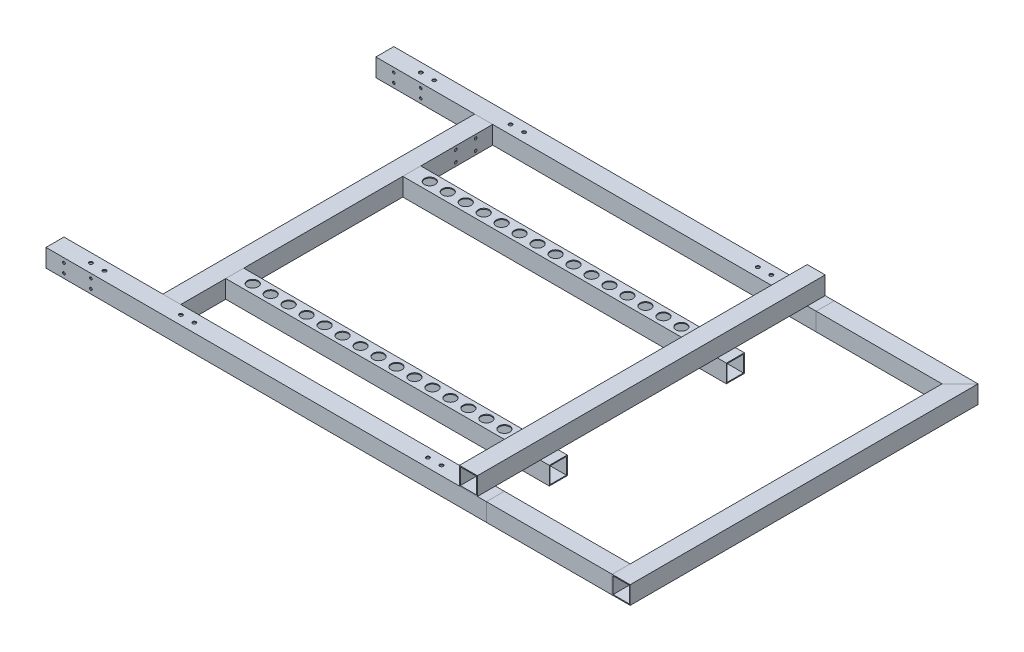
SolidWorks part; units mm, degrees
material "6063-O"
ref_plane "Front" through (0, 0, 0) normal (0, 0, 1) x (1, 0, 0)
ref_plane "Top" through (0, 0, 0) normal (0, 1, 0) x (1, 0, 0)
ref_plane "Right" through (0, 0, 0) normal (1, 0, 0) x (0, 0, -1)
sketch "草图1" plane through (0, 0, 0) normal (0, 1, 0) x (1, 0, 0)
  line L0 (0, 0) -> (500, 0)
  line L1 (0, -367) -> (500, -367)
  line L2 (0, -367) -> (0, -447)
  line L3 (0, -447) -> (500, -447)
  line L4 (130, 0) -> (130, -367)
  line L5 (130, -367) -> (130, -447)
  dimension "D1" = 447
  dimension "D2" = 80
  dimension "D3" = 500
  dimension "D4" = 130
other "铝管 20X20X1(1)"
ref_plane "基准面1" through (0, 0, 0) normal (1, 0, 0) x (0, 0, -1)
sketch "草图11" plane through (0, 0, 0) normal (1, 0, 0) x (0, 0, -1)
  line L1 (-10, -10) -> (10, -10)
  line L2 (-10, -10) -> (-10, 10)
  line L3 (-10, 10) -> (10, 10)
  line L4 (10, -10) -> (10, 10)
  line L5 (-10, -10) -> (10, 10) construction
  line L6 (-10, 10) -> (10, -10) construction
  line L7 (-9, -9) -> (9, -9)
  line L8 (-9, -9) -> (-9, 9)
  line L9 (-9, 9) -> (9, 9)
  line L10 (9, -9) -> (9, 9)
  line L11 (-9, -9) -> (9, 9) construction
  line L12 (-9, 9) -> (9, -9) construction
  point P0 (0, 0)
  point P6 (0, 0)
  point P11 (0, 0)
  dimension "D1" = 20
  dimension "D2" = 20
  dimension "D3" = 18
  dimension "D4" = 18
sketch "草图12" plane through (0, 0, 377) normal (0, 0, 1) x (1, 0, 0)
  line L0 (-10, -10) -> (-10, 10) construction
  line L1 (500, 10) -> (10, 10) construction
  circle A0 centre (30, 5) radius 1.5
  circle A1 centre (60, 5) radius 1.5
  circle A2 centre (30, -5) radius 1.5
  circle A3 centre (60, -5) radius 1.5
  dimension "D1" = 3
  dimension "D2" = 3
  dimension "D3" = 40
  dimension "D4" = 30
  dimension "D5" = 5
  dimension "D6" = 2
extrude "切除-拉伸1" cut sketch "草图12" against normal through all
sketch "草图13" plane through (0, 0, 0) normal (0, 1, 0) x (1, 0, 0)
  line L0 (500, 0) -> (650, 0)
  line L1 (500, 10) -> (500, -10) construction
  line L2 (500, -447) -> (650, -447)
  line L3 (500, -457) -> (500, -437) construction
  line L4 (500, -367) -> (650, -367)
  line L5 (500, -357) -> (500, -377) construction
  line L6 (650, -447) -> (650, 0)
  dimension "D1" = 150
other "铝管 20X20X1(2)"
ref_plane "基准面2" through (500, 0, 447) normal (1, 0, 0) x (0, 0, -1)
sketch "草图14" plane through (500, 0, 447) normal (1, 0, 0) x (0, 0, -1)
  line L1 (-10, -10) -> (10, -10)
  line L2 (-10, -10) -> (-10, 10)
  line L3 (-10, 10) -> (10, 10)
  line L4 (10, -10) -> (10, 10)
  line L5 (-10, -10) -> (10, 10) construction
  line L6 (-10, 10) -> (10, -10) construction
  line L7 (-9, -9) -> (9, -9)
  line L8 (-9, -9) -> (-9, 9)
  line L9 (-9, 9) -> (9, 9)
  line L10 (9, -9) -> (9, 9)
  line L11 (-9, -9) -> (9, 9) construction
  line L12 (-9, 9) -> (9, -9) construction
  point P0 (0, 0)
  point P6 (0, 0)
  point P11 (0, 0)
  dimension "D1" = 20
  dimension "D2" = 20
  dimension "D3" = 18
  dimension "D4" = 18
ref_plane "基准面3" through (0, 20, 0) normal (0, 1, 0) x (1, 0, 0)
sketch "草图15" plane through (0, 20, 0) normal (0, 1, 0) x (1, 0, 0)
  line L0 (480, 10) -> (480, -457)
  line L1 (500, 10) -> (0, 10) construction
  line L2 (-10, -457) -> (500, -457) construction
  dimension "D1" = 20
other "铝管 20X20X1(3)"
ref_plane "基准面4" through (480, 20, -10) normal (0, 0, 1) x (1, 0, 0)
sketch "草图16" plane through (480, 20, -10) normal (0, 0, 1) x (1, 0, 0)
  line L1 (-10, -10) -> (10, -10)
  line L2 (-10, -10) -> (-10, 10)
  line L3 (-10, 10) -> (10, 10)
  line L4 (10, -10) -> (10, 10)
  line L5 (-10, -10) -> (10, 10) construction
  line L6 (-10, 10) -> (10, -10) construction
  line L7 (-9, -9) -> (9, -9)
  line L8 (-9, -9) -> (-9, 9)
  line L9 (-9, 9) -> (9, 9)
  line L10 (9, -9) -> (9, 9)
  line L11 (-9, -9) -> (9, 9) construction
  line L12 (-9, 9) -> (9, -9) construction
  point P0 (0, 0)
  point P6 (0, 0)
  point P11 (0, 0)
  dimension "D1" = 20
  dimension "D2" = 20
  dimension "D3" = 18
  dimension "D4" = 18
sketch "草图17" plane through (140, 0, 0) normal (1, 0, 0) x (0, 0, -1)
  line L0 (-407, 10) -> (-407, -10) construction
  line L1 (-437, 10) -> (-377, 10) construction
  line L2 (-437, -10) -> (-377, -10) construction
  line L4 (-10, 0) -> (-81.1967, 0) construction
  line L5 (-10, 10) -> (-10, -10) construction
  line L6 (-40, 10) -> (-40, -10) construction
  line L7 (-357, 10) -> (-10, 10) construction
  line L8 (-357, -10) -> (-10, -10) construction
  circle A0 centre (-418, 6) radius 1.5 construction
  circle A1 centre (-418, -6) radius 1.5 construction
  circle A2 centre (-396, -6) radius 1.5 construction
  circle A3 centre (-396, 6) radius 1.5 construction
  circle A4 centre (-51, 6) radius 1.5
  circle A5 centre (-51, -6) radius 1.5
  circle A6 centre (-29, 6) radius 1.5
  circle A7 centre (-29, -6) radius 1.5
  dimension "D1" = 3
  dimension "D2" = 3
  dimension "D7" = 3
  dimension "D8" = 3
  dimension "D9" = 3
  dimension "D10" = 3
  dimension "D3" = 4
  dimension "D4" = 12
  dimension "D5" = 11
  dimension "D6" = 30
  dimension "D11" = 22
  dimension "D12" = 12
sketch "草图18" plane through (0, 0, 0) normal (0, 1, 0) x (1, 0, 0)
  line L0 (140, -100) -> (500, -100)
  line L1 (140, -357) -> (140, -10) construction
  line L2 (140, -297) -> (500, -297)
  line L3 (500, -357) -> (-10, -357) construction
  line L4 (500, -10) -> (0, -10) construction
  line L5 (500, 10) -> (500, -10) construction
  dimension "D1" = 60
  dimension "D2" = 90
other "铝管 20X20X1(4)"
ref_plane "基准面5" through (140, 0, 100) normal (1, 0, 0) x (0, 0, -1)
sketch "草图110" plane through (140, 0, 100) normal (1, 0, 0) x (0, 0, -1)
  line L1 (-10, -10) -> (10, -10)
  line L2 (-10, -10) -> (-10, 10)
  line L3 (-10, 10) -> (10, 10)
  line L4 (10, -10) -> (10, 10)
  line L5 (-10, -10) -> (10, 10) construction
  line L6 (-10, 10) -> (10, -10) construction
  line L7 (-9, -9) -> (9, -9)
  line L8 (-9, -9) -> (-9, 9)
  line L9 (-9, 9) -> (9, 9)
  line L10 (9, -9) -> (9, 9)
  line L11 (-9, -9) -> (9, 9) construction
  line L12 (-9, 9) -> (9, -9) construction
  point P0 (0, 0)
  point P6 (0, 0)
  point P11 (0, 0)
  dimension "D1" = 20
  dimension "D2" = 20
  dimension "D3" = 18
  dimension "D4" = 18
sketch "草图111" plane through (0, 10, 0) normal (0, 1, 0) x (1, 0, 0)
  line L0 (140, -100) -> (500, -100) construction
  line L1 (140, -90) -> (140, -110) construction
  line L2 (500, -90) -> (500, -110) construction
  line L3 (140, -297) -> (500, -297) construction
  line L4 (140, -287) -> (140, -307) construction
  line L5 (500, -287) -> (500, -307) construction
  line L6 (140, -357) -> (140, -10) construction
  circle A0 centre (160, -100) radius 6
  circle A1 centre (160, -297) radius 6
  circle A2 centre (180, -100) radius 6
  circle A3 centre (180, -297) radius 6
  circle A4 centre (200, -100) radius 6
  circle A5 centre (200, -297) radius 6
  circle A6 centre (220, -100) radius 6
  circle A7 centre (220, -297) radius 6
  circle A8 centre (240, -100) radius 6
  circle A9 centre (240, -297) radius 6
  circle A10 centre (260, -100) radius 6
  circle A11 centre (260, -297) radius 6
  circle A12 centre (280, -100) radius 6
  circle A13 centre (280, -297) radius 6
  circle A14 centre (300, -100) radius 6
  circle A15 centre (300, -297) radius 6
  circle A16 centre (320, -100) radius 6
  circle A17 centre (320, -297) radius 6
  circle A18 centre (340, -100) radius 6
  circle A19 centre (340, -297) radius 6
  circle A20 centre (360, -100) radius 6
  circle A21 centre (360, -297) radius 6
  circle A22 centre (380, -100) radius 6
  circle A23 centre (380, -297) radius 6
  circle A24 centre (400, -100) radius 6
  circle A25 centre (400, -297) radius 6
  circle A26 centre (420, -100) radius 6
  circle A27 centre (420, -297) radius 6
  circle A28 centre (440, -100) radius 6
  circle A29 centre (440, -297) radius 6
  dimension "D1" = 12
  dimension "D2" = 12
  dimension "D3" = 20
  dimension "D4" = 20
  dimension "D5" = 15
extrude "切除-拉伸3" cut sketch "草图111" against normal through all
sketch "草图112" plane through (0, 0, 307) normal (0, 0, 1) x (1, 0, 0)
  circle A0 centre (462, 0) radius 1.5
  dimension "D1" = 3
extrude "切除-拉伸4" cut sketch "草图112" against normal up to surface (217 mm away)
extrude "切除-拉伸5" cut sketch "草图17" against normal through all
sketch "草图113" plane through (0, 0, 457) normal (0, 0, 1) x (1, 0, 0)
  line L0 (660, -10) -> (660, 10) construction
  line L1 (660, 10) -> (500, 10) construction
  line L2 (500, 10) -> (500, -10) construction
  line L3 (500, -10) -> (660, -10) construction
  line L4 (-10, 10) -> (-10, -10) construction
  line L5 (-10, -10) -> (500, -10) construction
  line L6 (500, -10) -> (500, 10) construction
  line L7 (500, 10) -> (-10, 10) construction
  line L8 (660, -10) -> (660, 10)
  line L9 (660, 10) -> (500, 10)
  line L10 (500, 10) -> (500, -10)
  line L11 (500, -10) -> (660, -10)
  line L12 (-10, 10) -> (-10, -10)
  line L13 (-10, -10) -> (500, -10)
  line L14 (500, -10) -> (500, 10)
  line L15 (500, 10) -> (-10, 10)
  line L17 (418.5326, 10) -> (518.891, 10)
  line L18 (418.5326, 10) -> (418.5326, 44.5746)
  line L19 (418.5326, 44.5746) -> (518.891, 44.5746)
  line L20 (518.891, 10) -> (518.891, 44.5746)
  line M1 (-10, 10) -> (-10, -10)
  line M2 (-10, -10) -> (500, -10)
  line M3 (500, -10) -> (500, 10)
  line M4 (500, 10) -> (-10, 10)
extrude "切除-拉伸7" cut sketch "草图113" against normal up to surface (80 mm away) contours L15 M4 M1 M2 M3 | L11 L8 L9 M3 | L15 L20 L19 L18 up to face at (31.5, 5, 377)
sketch "草图114" plane through (0, -10, 0) normal (0, -1, 0) x (1, 0, 0)
  circle A0 centre (50, 367) radius 2
  circle A1 centre (65, 367) radius 2
  circle A2 centre (150, 367) radius 2
  circle A3 centre (165, 367) radius 2
  circle A4 centre (425, 367) radius 2
  circle A5 centre (440, 367) radius 2
  dimension "D1" = 4
  dimension "D2" = 4
  dimension "D3" = 4
  dimension "D4" = 4
  dimension "D5" = 4
  dimension "D6" = 4
extrude "切除-拉伸8" cut sketch "草图114" against normal through all
sketch "草图115" plane through (0, -10, 0) normal (0, -1, 0) x (1, 0, 0)
  circle A0 centre (50, 0) radius 2
  circle A1 centre (65, 0) radius 2
  circle A2 centre (150, 0) radius 2
  circle A3 centre (165, 0) radius 2
  circle A4 centre (440, 0) radius 2
  circle A5 centre (425, 0) radius 2
  dimension "D1" = 4
  dimension "D2" = 4
  dimension "D3" = 4
  dimension "D4" = 4
  dimension "D5" = 4
  dimension "D6" = 4
extrude "切除-拉伸9" cut sketch "草图115" against normal through all
sketch "草图116" plane through (0, 0, 377) normal (0, 0, 1) x (1, 0, 0)
  line L0 (-10, 10) -> (10, 10)
  line L1 (10, 10) -> (10, -10)
  line L2 (10, -10) -> (-10, -10)
  line L3 (-10, -10) -> (-10, 10)
extrude "切除-拉伸10" cut sketch "草图116" against normal through all
